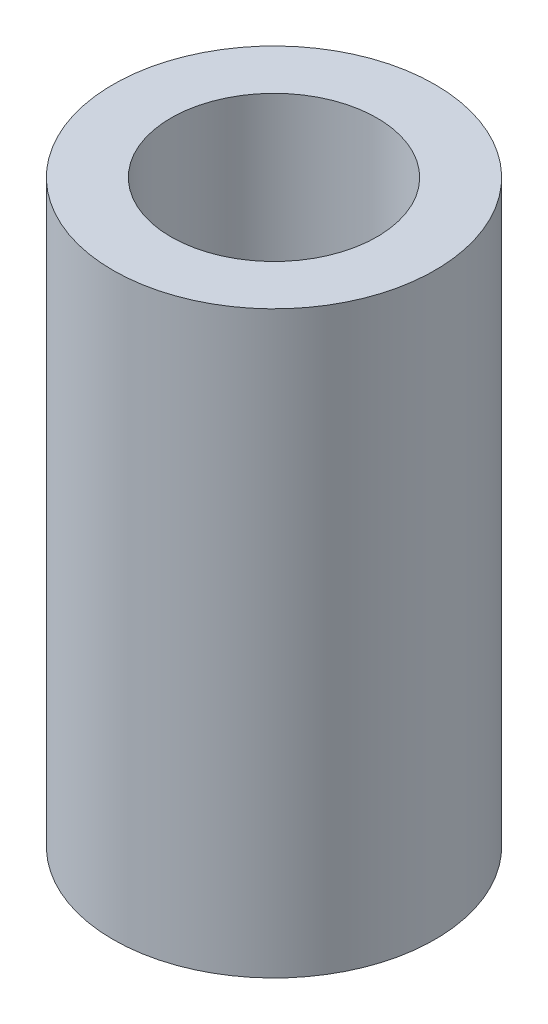
SolidWorks part; units mm, degrees
ref_plane "正面" through (0, 0, 0) normal (0, 0, 1) x (1, 0, 0)
ref_plane "平面" through (0, 0, 0) normal (0, 1, 0) x (1, 0, 0)
ref_plane "右側面" through (0, 0, 0) normal (1, 0, 0) x (0, 0, -1)
sketch "ｽｹｯﾁ1" plane through (0, 0, 0) normal (0, 1, 0) x (1, 0, 0)
  circle A0 centre (0, 0) radius 2.5
  circle A1 centre (0, 0) radius 1.6
  dimension "D1" = 3.2
  dimension "D2" = 5
extrude "ﾎﾞｽ - 押し出し1" add sketch "ｽｹｯﾁ1" along normal blind 9
